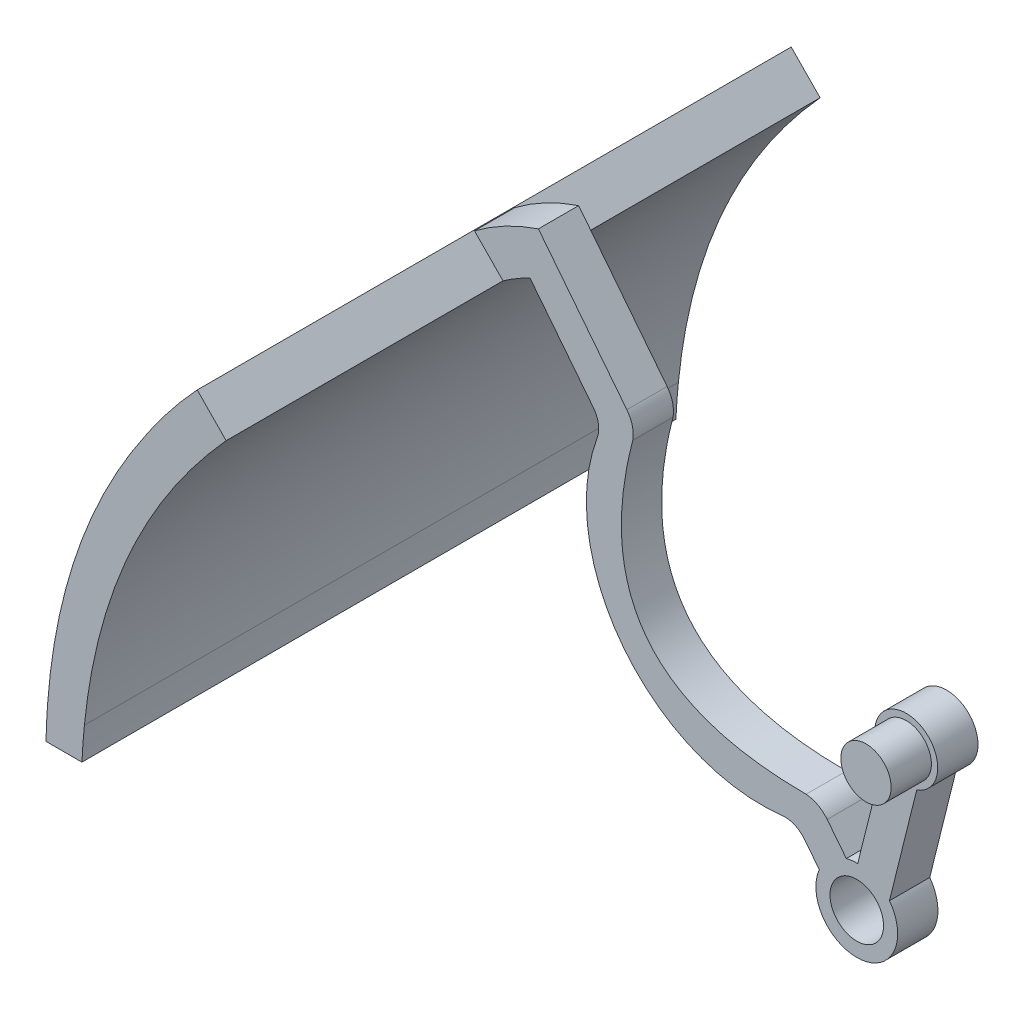
SolidWorks part; units mm, degrees
ref_plane "Front Plane" through (0, 0, 0) normal (0, 0, 1) x (1, 0, 0)
ref_plane "Top Plane" through (0, 0, 0) normal (0, 1, 0) x (1, 0, 0)
ref_plane "Right Plane" through (0, 0, 0) normal (1, 0, 0) x (0, 0, -1)
sketch "Sketch1" plane through (0, 0, 0) normal (0, 0, 1) x (1, 0, 0)
  line L4 (-16.2958, 0.6246) -> (-12.9075, 0.6246)
  line L6 (-15.8122, 3.1646) -> (-12.4433, 3.1646) construction
  line L7 (5.6776, 40.6472) -> (2.0317, 44.371) construction
  line L8 (2.0317, 44.371) -> (5.6776, 40.6472)
  line L9 (-15.8122, 3.1646) -> (-16.2958, 0.6246)
  line L10 (-12.4433, 3.1646) -> (-12.9075, 0.6246)
  line L11 (1.422, 48.6244) -> (-15.9394, 16.0823) construction
  line L12 (2.0317, 44.371) -> (-13.5164, 15.2278) construction
  line L13 (8.8419, 41.046) -> (1.422, 48.6244) construction
  line L14 (-8.3852, 11.2421) -> (8.8419, 41.046) construction
  line L15 (-10.8046, 12.1319) -> (5.6776, 40.6472) construction
  line L16 (-10.3254, 0.6246) -> (-8.3852, 11.2421) construction
  line L17 (-12.4433, 3.1646) -> (-10.8046, 12.1319) construction
  line L18 (-18.8814, 0.6246) -> (-10.3254, 0.6246) construction
  spline S1 degree 1 poles (-13.5164, 15.2278) (-15.8122, 3.1646) knots 0 0 1 1 construction
  spline S8 degree 3 poles (-15.9394, 16.0823) (-16.1844, 14.7942) (-16.6747, 12.2179) (-17.4101, 8.3535) (-17.9442, 5.5474) (-18.3138, 3.6061) (-18.559, 2.318) (-18.7605, 1.2596) (-18.8814, 0.6246) knots -0.003069 -0.003069 -0.003069 -0.003069 0.000865 0.004799 0.008732 0.009434 0.010727 0.012666 0.012666 0.012666 0.012666
  spline S12 degree 3 poles (2.0317, 44.371) (1.5451, 43.8493) (0.584, 42.7847) (-1.2279, 40.6343) (-4.2059, 36.7376) (-7.8686, 30.8427) (-11.2851, 23.2592) (-12.8911, 17.9284) (-13.5164, 15.2278) knots 0.192223 0.192223 0.192223 0.192223 0.287167 0.382111 0.572 0.951777 1.331554 1.711331 1.711331 1.711331 1.711331
  spline S13 degree 3 poles (-13.5164, 15.2278) (-13.7077, 14.2225) (-14.0902, 12.212) (-14.6641, 9.1962) (-15.2381, 6.1804) (-15.6209, 4.1699) (-15.8122, 3.1646) knots -0.002683 -0.002683 -0.002683 -0.002683 0.000387 0.003457 0.006527 0.009597 0.009597 0.009597 0.009597
  spline S14 degree 3 poles (-12.4433, 3.1646) (-12.3067, 3.9119) (-11.897, 6.1537) (-11.3508, 9.1428) (-10.9412, 11.3846) (-10.8046, 12.1319) knots 0.002076 0.002076 0.002076 0.002076 0.004355 0.008913 0.011192 0.011192 0.011192 0.011192
  spline S15 degree 3 poles (-10.8046, 12.1319) (-10.1318, 14.8139) (-8.4286, 20.0889) (-4.7699, 27.6024) (-0.8821, 33.37) (2.6966, 37.6291) (4.6636, 39.6689) (5.6776, 40.6472) knots -0.595137 -0.595137 -0.595137 -0.595137 -0.254899 0.085339 0.425577 0.595696 0.765815 0.765815 0.765815 0.765815
  dimension "D2" = 2.54
extrude "Boss-Extrude1" add sketch "Sketch1" along normal blind 74.93 contours S15 L8 S12 S13 L9 L4 L10 S14
ref_plane "Plane1" through (0, 0, 37.465) normal (0, 0, -1) x (-1, 0, 0)
sketch "Sketch4" plane through (0, 0, 37.465) normal (0, 0, -1) x (-1, 0, 0)
  line L0 (-2.0317, 44.371) -> (-5.6776, 40.6472) construction
  line L1 (-2.0317, 44.371) -> (-5.6776, 40.6472)
  line L5 (-10.1449, 48.562) -> (-12.3422, 43.9333)
  line L6 (-40.0025, 32.4269) -> (-55.4917, 2.9233) construction
  line L7 (-44.5004, 34.7882) -> (-59.9895, 5.2847) construction
  arc A0 (-5.6776, 40.6472) -> (-12.3422, 43.9333) centre (-19.2461, 21.53) ccw
  arc A1 (-2.0871, 44.3144) -> (-10.1449, 48.562) centre (-19.2461, 21.53) ccw
  arc A2 (-2.7374, 44.7899) -> (-44.5004, 34.7882) centre (-19.2461, 21.53) ccw construction
  arc A3 (-5.6776, 40.6472) -> (-40.0025, 32.4269) centre (-19.2461, 21.53) ccw construction
  dimension "D1" = 5.08
extrude "Boss-Extrude4" add sketch "Sketch4" along normal blind 2.54 and the other way blind 2.54
sketch "Sketch5" plane through (0, 0, 34.925) normal (0, 0, -1) x (-1, 0, 0)
  circle A0 centre (-9.1835, 45.3695) radius 1.4292
sketch "Sketch8" plane through (0, 0, 0) normal (0, 0, -1) x (-1, 0, 0)
  line L0 (12.2, 0.6287) -> (16.8437, 0.6287)
  line L1 (-5.6776, 40.6472) -> (-2.0317, 44.371)
  spline S0 degree 2 poles (-5.6776, 40.6472) (9.879, 23.5215) (12.2, 0.6287) knots 0 0 0 1 1 1
  spline S1 degree 2 poles (-2.0317, 44.371) (15.0089, 25.4946) (16.8437, 0.6287) knots 0 0 0 1 1 1
extrude "Boss-Extrude6" add sketch "Sketch8" against normal up to vertex (74.93 mm away) up to point (5.6776, 40.6472, 74.93)
sketch "Sketch7" plane through (0, 0, 0) normal (0, 0, -1) x (-1, 0, 0)
  circle A0 centre (14.0387, 3.7592) radius 1.25
  dimension "D1" = 2.5
sketch "Sketch9" plane through (0, 0, 74.93) normal (0, 0, 1) x (1, 0, 0)
  line L6 (5.6776, 40.6472) -> (2.0317, 44.371)
  line L7 (-16.8437, 0.6287) -> (-16.295, 0.6287)
  line L8 (-16.295, 0.6287) -> (-16.2958, 0.6246)
  line L9 (-16.2958, 0.6246) -> (-12.9075, 0.6246)
  line L10 (-12.9075, 0.6246) -> (-12.9068, 0.6287)
  line L11 (-12.9068, 0.6287) -> (-12.2, 0.6287)
  line L12 (5.6776, 40.6472) -> (2.0317, 44.371)
  line L13 (-16.8437, 0.6287) -> (-16.295, 0.6287)
  line L14 (-16.295, 0.6287) -> (-16.2958, 0.6246)
  line L15 (-16.2958, 0.6246) -> (-12.9075, 0.6246)
  line L16 (-12.9075, 0.6246) -> (-12.9068, 0.6287)
  line L17 (-12.9068, 0.6287) -> (-12.2, 0.6287)
  parabola Q2 (-12.2, 0.6287) -> (5.6776, 40.6472) focus (23.6762, 8.2321) apex (-6.8175, 21.519)
  parabola Q3 (-4.5365, 36.0597) -> (-16.8437, 0.6287) focus (20.2122, 9.2238) apex (-12.0584, 21.9349)
  parabola Q4 (-12.2, 0.6287) -> (5.6776, 40.6472) focus (23.6762, 8.2321) apex (-6.8175, 21.519)
  parabola Q5 (-4.5365, 36.0597) -> (-16.8437, 0.6287) focus (20.2122, 9.2238) apex (-12.0584, 21.9349)
  spline S1 degree 3 poles (-1957.9807, -2226.1255) (123.2572, 102.2338) (30.2091, 77.9435) (-1.2279, 40.6343) (-108.5489, -99.7905) (407.0769, -585.0968) (2829.7881, -777.2635) knots -6.017137 -6.017137 -6.017137 -6.017137 0.287167 0.382111 0.572 24.238034 24.238034 24.238034 24.238034 only from (2.0317, 44.371) to (-4.5365, 36.0597)
  spline S2 degree 3 poles (2.0317, 44.371) (1.5451, 43.8493) (0.584, 42.7847) (-1.2279, 40.6343) (-2.9419, 38.3915) (-4.1401, 36.6553) (-4.5365, 36.0597) knots 0.192223 0.192223 0.192223 0.192223 0.287167 0.382111 0.572 0.669689 0.669689 0.669689 0.669689
  dimension "D1" = 0
extrude "Cut-Extrude2" [suppressed] cut sketch "Sketch9" against normal blind 0.508
mirror "Mirror4" [suppressed] about plane through (0, 0, 37.465) normal (0, 0, -1)
sketch "Sketch10" plane through (0, 0, 74.93) normal (0, 0, 1) x (1, 0, 0)
  line L0 (-17.0442, -3.569) -> (-12.512, -3.569)
  line L1 (-16.8437, 0.6287) -> (-12.2, 0.6287)
  parabola Q0 (5.6776, 40.6472) -> (-12.2, 0.6287) focus (23.6762, 8.2321) apex (-6.8175, 21.519) construction
  parabola Q1 (-16.8437, 0.6287) -> (-4.5365, 36.0597) focus (20.2122, 9.2238) apex (-12.0584, 21.9349) construction
  parabola Q2 (-12.2, 0.6287) -> (-12.512, -3.569) focus (23.6762, 8.2321) apex (-6.8175, 21.519)
  parabola Q3 (-17.0442, -3.569) -> (-16.8437, 0.6287) focus (20.2122, 9.2238) apex (-12.0584, 21.9349)
  line M5 (-16.8437, 0.6287) -> (-16.295, 0.6287)
  line M6 (-16.295, 0.6287) -> (-16.2958, 0.6246)
  line M7 (-16.2958, 0.6246) -> (-12.9075, 0.6246)
  line M8 (-12.9075, 0.6246) -> (-12.9068, 0.6287)
  line M9 (-12.9068, 0.6287) -> (-12.2, 0.6287)
extrude "Boss-Extrude7" add sketch "Sketch10" against normal up to vertex (74.93 mm away) contours Q3 L0 Q2 M9 M8 M7 M6 M5
sketch "Sketch11" plane through (0, 0, 37.465) normal (0, 0, -1) x (-1, 0, 0)
  line L0 (-10.1449, 48.562) -> (-21.3007, 34.3832)
  line L2 (-45.5817, -3.7263) -> (-43.7063, -1.3428)
  line L3 (-6.6617, 45.7399) -> (-10.1449, 48.562)
  line L7 (-48.99, -0.8091) -> (-45.5817, -3.7263) construction
  line L8 (-56.5487, 14.8705) -> (-50.307, -5.7975) construction
  line L9 (-46.5777, 2.2568) -> (-48.99, -0.8091)
  line L10 (-17.0779, 32.5012) -> (-6.6617, 45.7399)
  line L12 (-54.4314, 15.3996) -> (-50.4238, -0.6395)
  line L13 (-58.6667, 14.3442) -> (-54.4314, -2.6979)
  circle A0 centre (-50.307, -5.7975) radius 58.9903 construction
  circle A1 centre (-50.307, -5.7975) radius 3.3782
  arc A2 (-48.99, -0.8091) -> (-50.4238, -0.6395) centre (-50.307, -5.7975) ccw
  arc A3 (-54.4314, -2.6979) -> (-45.5817, -3.7263) centre (-50.307, -5.7975) ccw
  arc A4 (-17.5615, 29.4393) -> (-40.8442, -0.1523) centre (-38.291, 21.794) cw
  arc A6 (-46.5777, 2.2568) -> (-43.9212, 3.6829) centre (-43.6155, -0.0739) cw
  arc A7 (-21.3007, 34.3832) -> (-22.0524, 31.4094) centre (-18.3385, 32.0525) ccw
  arc A8 (-17.5615, 29.4393) -> (-17.0779, 32.5012) centre (-14.5827, 30.5379) cw
  arc A9 (-40.8442, -0.1523) -> (-43.7063, -1.3428) centre (-41.2111, -3.3061) ccw
  circle A10 centre (-50.307, -5.7975) radius 23.9776 construction
  arc A12 (-54.4314, 15.3996) -> (-58.6667, 14.3442) centre (-56.5487, 14.8705) ccw
  spline S0 degree 3 poles (-74296.1296, 108661.1073) (-486.9364, -131.9838) (-102.935, 126.3414) (-7.6642, 35.0815) (-4.4986, 31.5222) (-0.6932, 26.4572) (242.2133, -396.7002) (-5091.4001, -3279.0146) (-34422.7676, 126984.773) knots -16.391332 -16.391332 -16.391332 -16.391332 -0.52668 -0.327365 -0.128051 0.071264 0.469894 61.007885 61.007885 61.007885 61.007885 only from (-12.4386, 39.4335) to (5.0009, 14.7184) construction
  spline S1 degree 3 poles (-12.4386, 39.4335) (-12.0211, 39.084) (-10.3869, 37.6895) (-7.6642, 35.0815) (-4.4986, 31.5222) (-0.6932, 26.4572) (2.5394, 20.8257) (4.4136, 16.3237) (5.0009, 14.7184) knots -0.592829 -0.592829 -0.592829 -0.592829 -0.52668 -0.327365 -0.128051 0.071264 0.469894 0.685568 0.685568 0.685568 0.685568
  spline S2 degree 2 poles (-43.9212, 3.6829) (-14.804, 3.6854) (-22.0524, 31.4094) knots 0 0 0 1 1 1
  point P28 (-18.2255, 31.0426)
  dimension "D1" = 6.7564
  dimension "D2" = 3.175
  dimension "D3" = 55
  dimension "D4" = 21.59
extrude "Boss-Extrude8" add sketch "Sketch11" along normal mid plane 5.08
sketch "Sketch13" plane through (0, 0, 40.005) normal (0, 0, 1) x (1, 0, 0)
  circle A0 centre (56.5487, 14.8705) radius 3.9713
  arc A1 (58.6667, 14.3442) -> (54.4314, 15.3996) centre (56.5487, 14.8705) ccw construction
extrude "Boss-Extrude10" add sketch "Sketch13" against normal up to surface (5.08 mm away)
sketch "Sketch12" plane through (0, 0, 40.005) normal (0, 0, 1) x (1, 0, 0)
  circle A0 centre (56.5487, 14.8705) radius 3.175
  arc A1 (57.8665, 11.1243) -> (53.6271, 12.1807) centre (56.5487, 14.8705) ccw construction
  dimension "D1" = 6.35
extrude "Boss-Extrude9" add sketch "Sketch12" along normal blind 5.08
